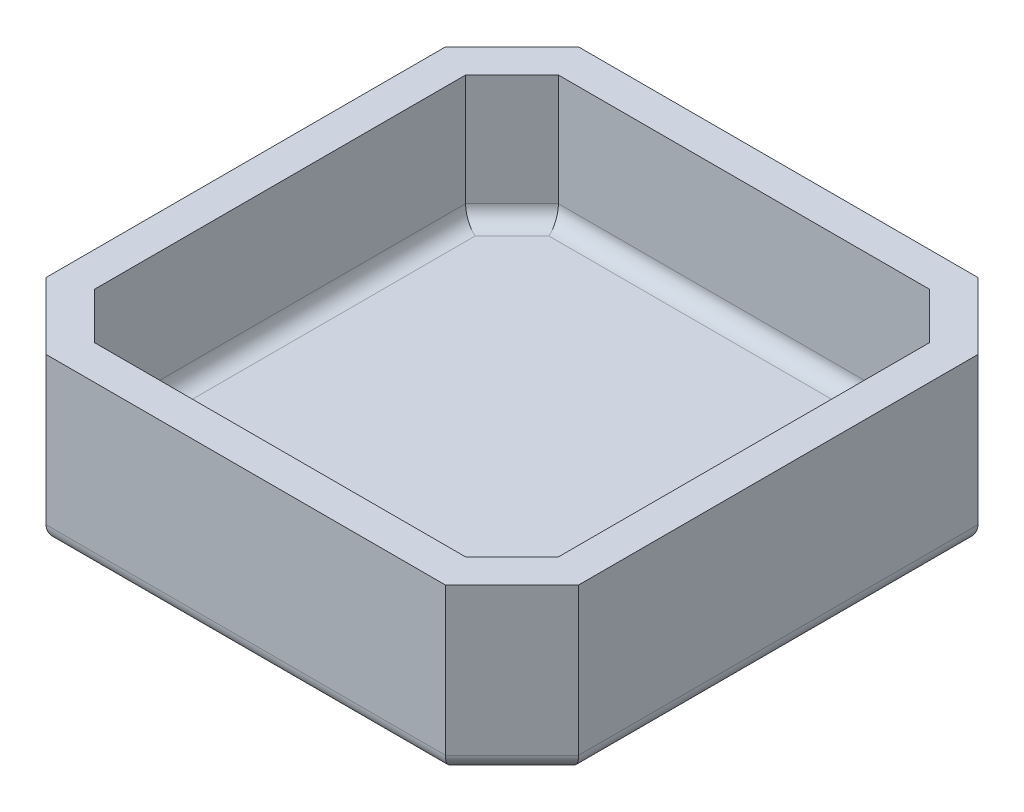
SolidWorks part; units mm, degrees
ref_plane "Ebene vorne" through (0, 0, 0) normal (0, 0, 1) x (1, 0, 0)
ref_plane "Ebene oben" through (0, 0, 0) normal (0, 1, 0) x (1, 0, 0)
ref_plane "Ebene rechts" through (0, 0, 0) normal (1, 0, 0) x (0, 0, -1)
sketch "Sketch1" plane through (0, 0, 0) normal (0, 1, 0) x (1, 0, 0)
  line L1 (-32.5, -32.5) -> (32.5, -32.5)
  line L2 (-32.5, -32.5) -> (-32.5, 32.5)
  line L3 (-32.5, 32.5) -> (32.5, 32.5)
  line L4 (32.5, -32.5) -> (32.5, 32.5)
  line L5 (-32.5, -32.5) -> (32.5, 32.5) construction
  line L6 (-32.5, 32.5) -> (32.5, -32.5) construction
  point P0 (0, 0)
  dimension "D1" = 65
extrude "Extrude1" add sketch "Sketch1" along normal blind 4.4
chamfer "Chamfer1" distance 8.125 angle 45 4 edges at (-32.5, 2.2, -32.5) (32.5, 2.2, -32.5) (32.5, 2.2, 32.5) (-32.5, 2.2, 32.5)
sketch "Sketch2" plane through (0, 4.4, 0) normal (0, 1, 0) x (1, 0, 0)
  line L0 (-28.3, 22.6353) -> (-28.3, -22.6353)
  line L1 (-28.3, -22.6353) -> (-22.6353, -28.3)
  line L2 (-22.6353, -28.3) -> (15.1829, -28.3)
  line L3 (15.1829, -28.3) -> (22.6353, -28.3)
  line L4 (22.6353, -28.3) -> (28.3, -22.6353)
  line L5 (28.3, -22.6353) -> (28.3, 22.6353)
  line L6 (28.3, 22.6353) -> (22.6353, 28.3)
  line L7 (22.6353, 28.3) -> (-22.6353, 28.3)
  line L8 (-22.6353, 28.3) -> (-28.3, 22.6353)
  line L9 (-32.5, 24.375) -> (-32.5, -24.375) construction
  line L10 (24.375, 32.5) -> (-24.375, 32.5) construction
  line L11 (32.5, -24.375) -> (32.5, 24.375) construction
  line L12 (-24.375, -32.5) -> (24.375, -32.5) construction
  line L14 (-32.5, -24.375) -> (-24.375, -32.5) construction
  line L16 (-24.375, 32.5) -> (-32.5, 24.375) construction
  line L17 (32.5, 24.375) -> (24.375, 32.5) construction
  line L18 (24.375, -32.5) -> (32.5, -24.375) construction
  line M10 (24.375, 32.5) -> (-24.375, 32.5)
  line M11 (-24.375, 32.5) -> (-32.5, 24.375)
  line M12 (-32.5, 24.375) -> (-32.5, -24.375)
  line M13 (-32.5, -24.375) -> (-24.375, -32.5)
  line M14 (-24.375, -32.5) -> (24.375, -32.5)
  line M15 (24.375, -32.5) -> (32.5, -24.375)
  line M16 (32.5, -24.375) -> (32.5, 24.375)
  line M17 (32.5, 24.375) -> (24.375, 32.5)
  dimension "D1" = 4.2
  dimension "D2" = 4.2
  dimension "D3" = 4.2
  dimension "D4" = 4.2
  dimension "D5" = 4.2
  dimension "D6" = 4.2
  dimension "D7" = 4.2
  dimension "D8" = 4.2
extrude "Extrude2" add sketch "Sketch2" along normal blind 15.6 contours L8 L7 L6 L5 L4 L3 L2 L1 L0 M17 M10 M11 M12 M13 M14 M15 M16
fillet "Fillet1" radius 2 16 edges at (-25.4677, 4.4, -25.4677) (-28.3, 4.4, 0) (-25.4677, 4.4, 25.4677) (0, 4.4, 28.3) (25.4677, 4.4, 25.4677) (28.3, 4.4, 0) (25.4677, 4.4, -25.4677) (0, 4.4, -28.3) (-32.5, 0, 0) (-28.4375, 0, 28.4375) (0, 0, 32.5) (28.4375, 0, 28.4375) (32.5, 0, 0) (28.4375, 0, -28.4375) (0, 0, -32.5) (-28.4375, 0, -28.4375)
